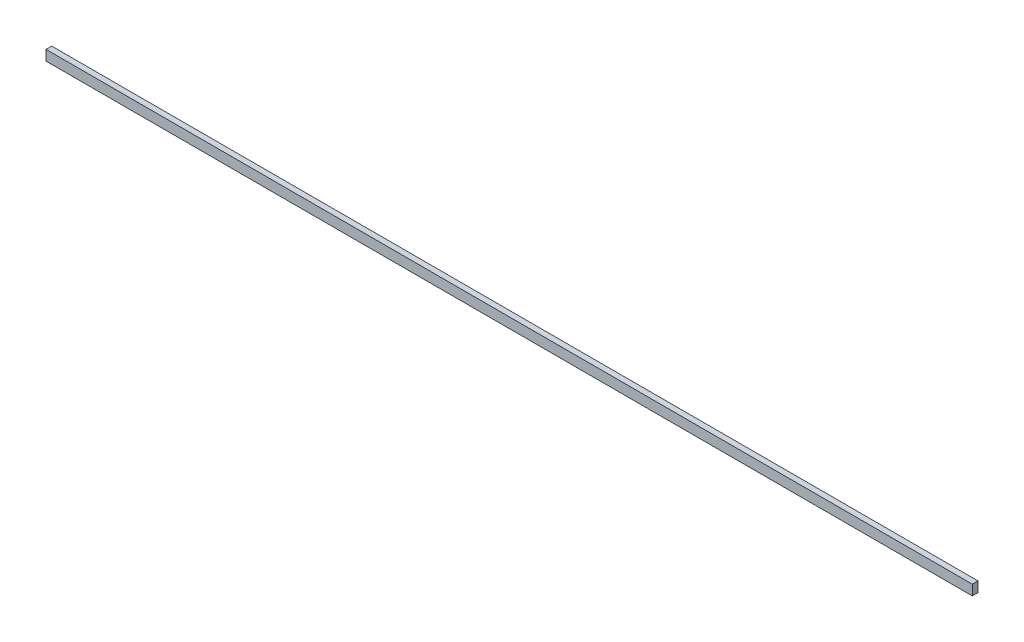
SolidWorks part; units mm, degrees
material "Фанера"
ref_plane "Front Plane" through (0, 0, 0) normal (0, 0, 1) x (1, 0, 0)
ref_plane "Top Plane" through (0, 0, 0) normal (0, 1, 0) x (1, 0, 0)
ref_plane "Right Plane" through (0, 0, 0) normal (1, 0, 0) x (0, 0, -1)
sketch "Эскиз2" plane through (0, 0, 0) normal (0, 0, 1) x (1, 0, 0)
  line L1 (-227.8, -2.5) -> (227.8, -2.5)
  line L2 (-227.8, -2.5) -> (-227.8, 2.5)
  line L3 (-227.8, 2.5) -> (227.8, 2.5)
  line L4 (227.8, -2.5) -> (227.8, 2.5)
  line L5 (-227.8, -2.5) -> (227.8, 2.5) construction
  line L6 (-227.8, 2.5) -> (227.8, -2.5) construction
  point P0 (0, 0)
  point P5 (227.8, 0)
  dimension "D1" = 5
  dimension "D2" = 455.6
extrude "Бобышка-Вытянуть1" add sketch "Эскиз2" along normal mid plane 2.8
equation "\"D2@Эскиз2\"=461.20мм-2.8*2"
